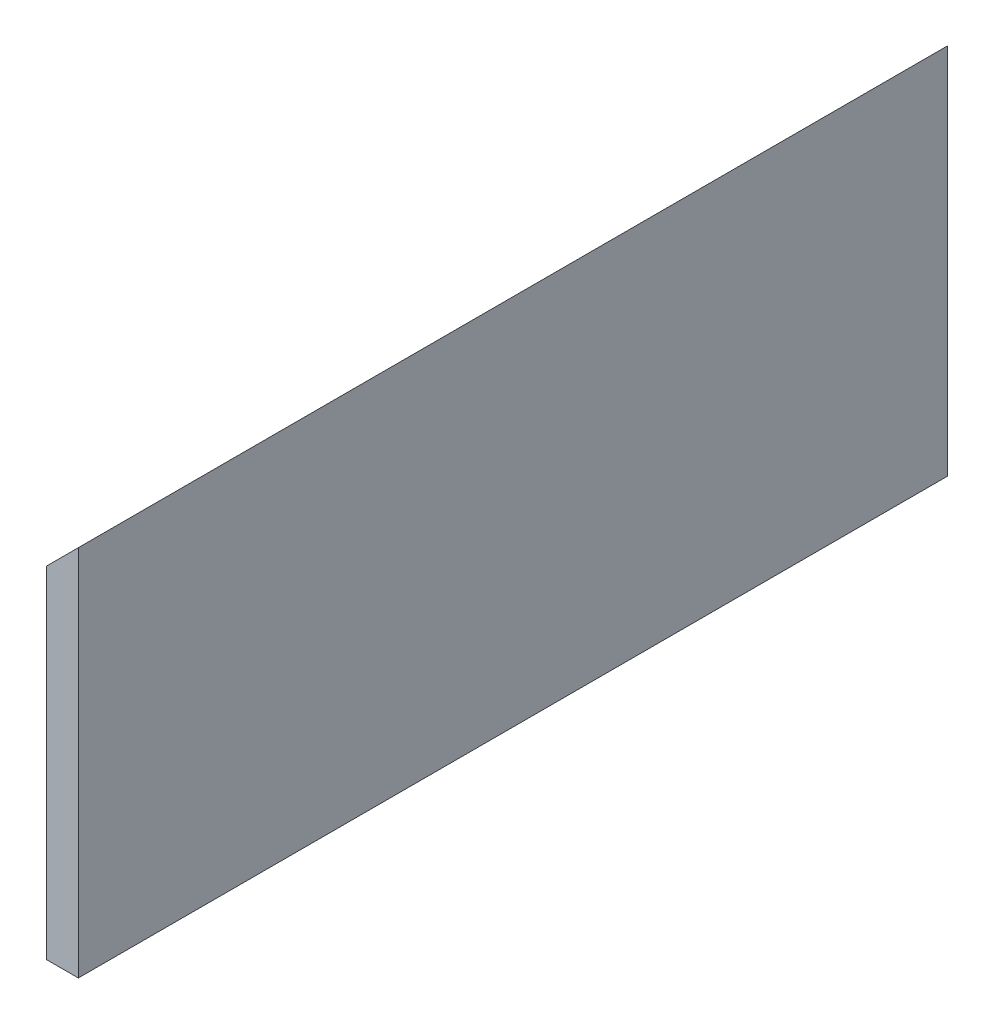
SolidWorks part; units mm, degrees
ref_plane "Ön Düzlem" through (0, 0, 0) normal (0, 0, 1) x (1, 0, 0)
ref_plane "Üst Düzlem" through (0, 0, 0) normal (0, 1, 0) x (1, 0, 0)
ref_plane "Sağ Düzlem" through (0, 0, 0) normal (1, 0, 0) x (0, 0, -1)
sketch "Çizim1" plane through (0, 0, 0) normal (1, 0, 0) x (0, 0, -1)
  line L0 (0, 0) -> (0, 117.95)
  line L1 (0, 117.95) -> (275, 117.95)
  line L2 (275, 117.95) -> (275, 0)
  line L3 (275, 0) -> (0, 0)
  dimension "D1" = 117.95
  dimension "D2" = 275
extrude "Yükseklik-Ekstrüzyon1" add sketch "Çizim1" along normal blind 10
sketch "Çizim2" plane through (0, 0, -275) normal (0, 0, -1) x (-1, 0, 0)
  line L0 (-10, 117.95) -> (0, 107.95)
  line L1 (-10, 117.95) -> (0, 117.95)
  line L2 (0, 117.95) -> (0, 107.95)
  line L3 (0, 0) -> (0, 117.95) construction
  dimension "D1" = 45
extrude "Kes-Ekstrüzyon1" cut sketch "Çizim2" against normal through all
